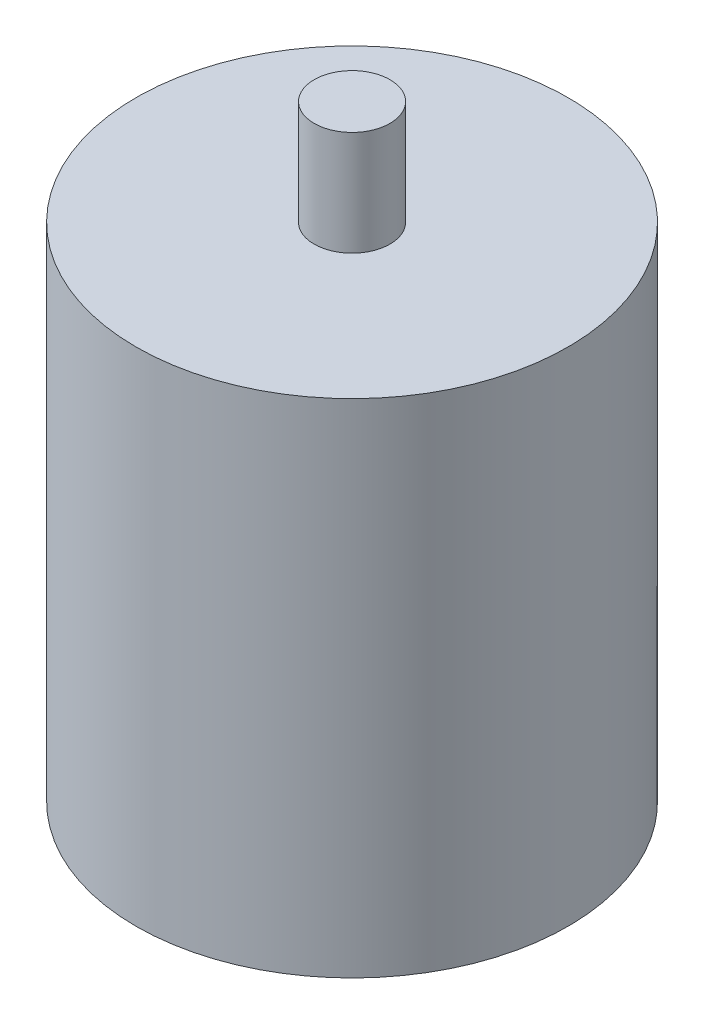
SolidWorks part; units mm, degrees
ref_plane "Front Plane" through (0, 0, 0) normal (0, 0, 1) x (1, 0, 0)
ref_plane "Top Plane" through (0, 0, 0) normal (0, 1, 0) x (1, 0, 0)
ref_plane "Right Plane" through (0, 0, 0) normal (1, 0, 0) x (0, 0, -1)
sketch "Sketch1" plane through (0, 0, 0) normal (0, 1, 0) x (1, 0, 0)
  circle A0 centre (0, 0) radius 14.25
extrude "Boss-Extrude1" add sketch "Sketch1" along normal blind 33.1
sketch "Sketch2" plane through (0, 0, 0) normal (0, 1, 0) x (1, 0, 0)
  circle A0 centre (0, 0) radius 2.5
extrude "Boss-Extrude2" add sketch "Sketch2" along normal blind 40
